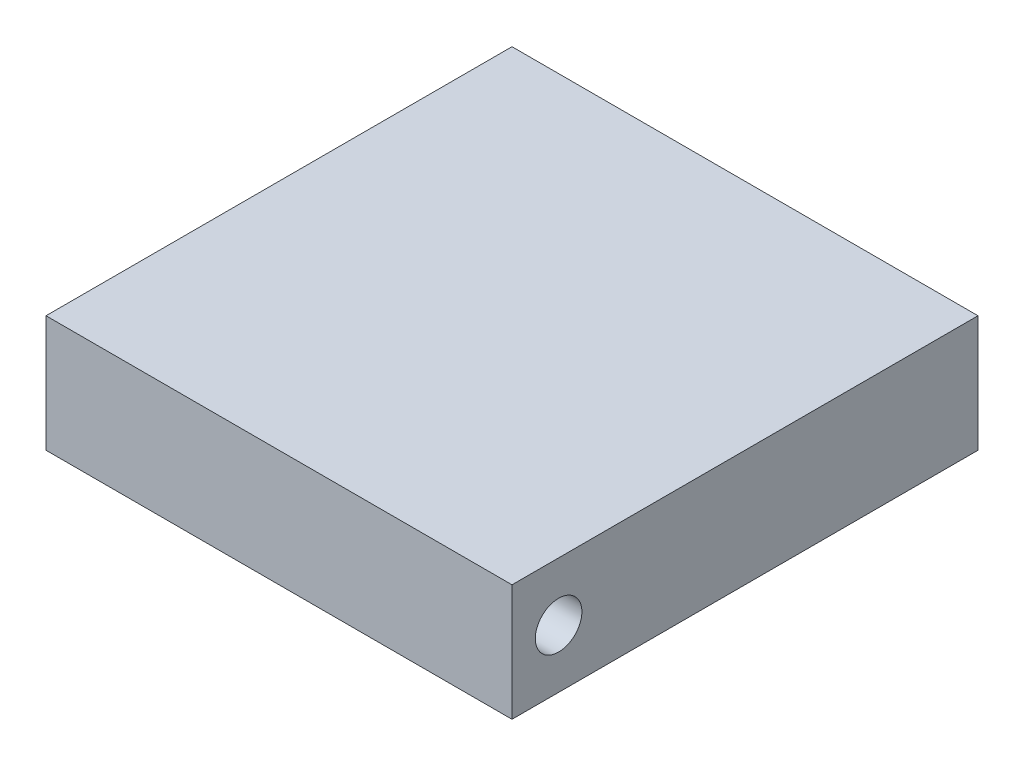
SolidWorks part; units mm, degrees
ref_plane "Front Plane" through (0, 0, 0) normal (0, 0, 1) x (1, 0, 0)
ref_plane "Top Plane" through (0, 0, 0) normal (0, 1, 0) x (1, 0, 0)
ref_plane "Right Plane" through (0, 0, 0) normal (1, 0, 0) x (0, 0, -1)
sketch "Sketch1" plane through (0, 0, 0) normal (0, 1, 0) x (1, 0, 0)
  line L1 (-10, 10) -> (10, 10)
  line L2 (-10, 10) -> (-10, -10)
  line L3 (-10, -10) -> (10, -10)
  line L4 (10, 10) -> (10, -10)
  line L5 (-10, 10) -> (10, -10) construction
  line L6 (-10, -10) -> (10, 10) construction
  point P0 (0, 0)
  dimension "D1" = 20
  dimension "D2" = 20
extrude "Boss-Extrude1" add sketch "Sketch1" along normal mid plane 5
sketch "Sketch2" plane through (10, 0, 0) normal (1, 0, 0) x (0, 0, -1)
  line L0 (-1000, 0) -> (49000, 0) construction
  line L1 (-10, 2.5) -> (-10, -2.5) construction
  circle A0 centre (-8, 0) radius 1
  dimension "D1" = 2
  dimension "D2" = 2
extrude "Cut-Extrude1" cut sketch "Sketch2" against normal up to next
